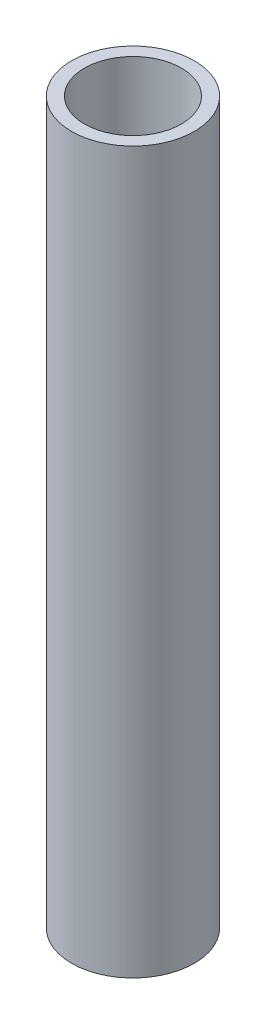
SolidWorks part; units mm, degrees
ref_plane "Front Plane" through (0, 0, 0) normal (0, 0, 1) x (1, 0, 0)
ref_plane "Top Plane" through (0, 0, 0) normal (0, 1, 0) x (1, 0, 0)
ref_plane "Right Plane" through (0, 0, 0) normal (1, 0, 0) x (0, 0, -1)
sketch "Sketch1" plane through (0, 0, 0) normal (0, 1, 0) x (1, 0, 0)
  circle A0 centre (0, 0) radius 1.702
  circle A1 centre (0, 0) radius 1.346
extrude "Boss-Extrude1" add sketch "Sketch1" along normal blind 20
